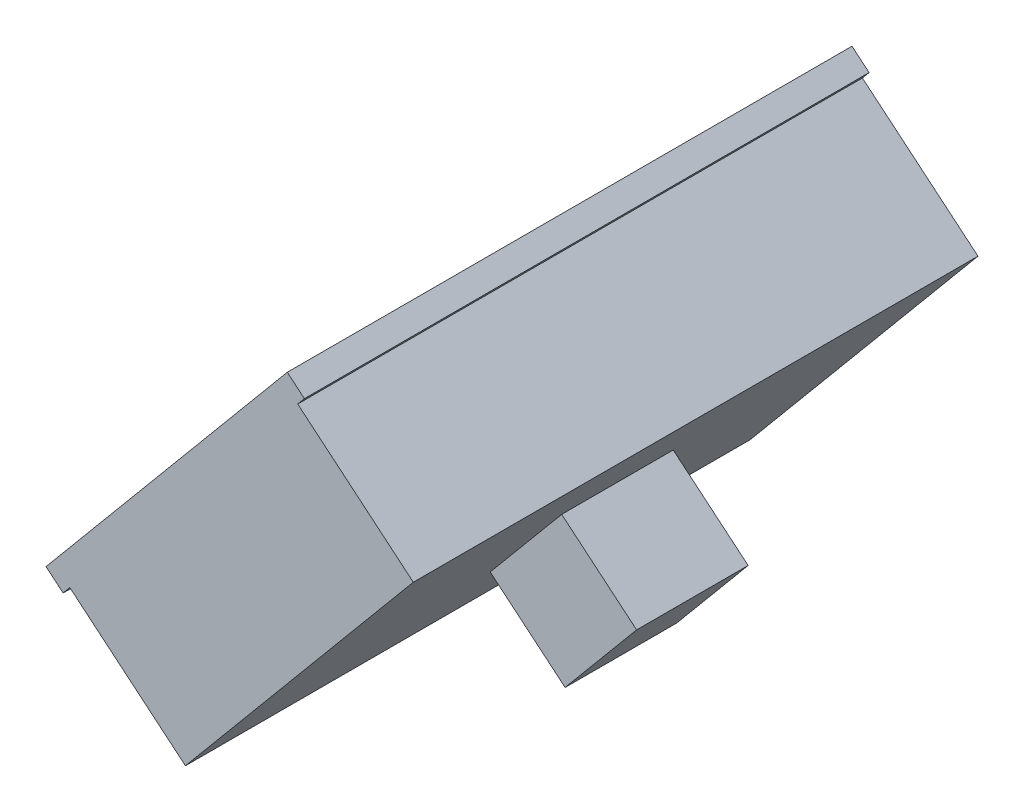
SolidWorks part; units mm, degrees
ref_plane "Front Plane" through (0, 0, 0) normal (0, 0, 1) x (1, 0, 0)
ref_plane "Top Plane" through (0, 0, 0) normal (0, 1, 0) x (1, 0, 0)
ref_plane "Right Plane" through (0, 0, 0) normal (1, 0, 0) x (0, 0, -1)
ref_plane "Plano_Front Plane_-128_1" through (0, 0, -128.1) normal (0, 0, 1) x (1, 0, 0)
sketch "Croquis_mb" plane through (0, 0, -128.1) normal (0, 0, 1) x (1, 0, 0)
  line L0 (-123.544, 167.0717) -> (-106.2386, 187.7967)
  line L1 (-106.2386, 187.7967) -> (-105.0105, 186.7712)
  line L2 (-105.0105, 186.7712) -> (-122.3158, 166.0462)
  line L3 (-122.3158, 166.0462) -> (-123.544, 167.0717)
extrude "MB" add sketch "Croquis_mb" along normal blind 40.5
sketch "Croquis_cam" plane through (0, 0, -128.1) normal (0, 0, 1) x (1, 0, 0)
  line L0 (-121.8351, 166.6219) -> (-105.4912, 186.1955)
  line L1 (-105.4912, 186.1955) -> (-97.2012, 179.2734)
  line L2 (-97.2012, 179.2734) -> (-113.5451, 159.6998)
  line L3 (-113.5451, 159.6998) -> (-121.8351, 166.6219)
extrude "CAM" add sketch "Croquis_cam" along normal blind 40.5
ref_plane "Plano_Front Plane_-103_85" through (0, 0, -103.85) normal (0, 0, 1) x (1, 0, 0)
sketch "Croquis_lente" plane through (0, 0, -103.85) normal (0, 0, 1) x (1, 0, 0)
  line L0 (-107.9369, 166.4162) -> (-102.8094, 172.5569)
  line L1 (-102.8094, 172.5569) -> (-97.4362, 168.0704)
  line L2 (-97.4362, 168.0704) -> (-102.5638, 161.9296)
  line L3 (-102.5638, 161.9296) -> (-107.9369, 166.4162)
extrude "Lente" add sketch "Croquis_lente" against normal blind 8
